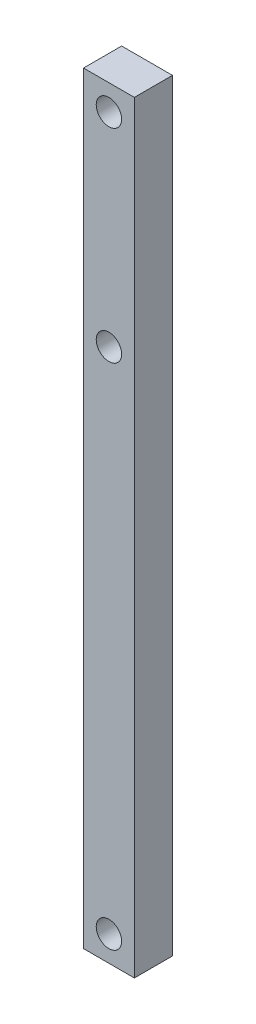
SolidWorks part; units mm, degrees
ref_plane "Front Plane" through (0, 0, 0) normal (0, 0, 1) x (1, 0, 0)
ref_plane "Top Plane" through (0, 0, 0) normal (0, 1, 0) x (1, 0, 0)
ref_plane "Right Plane" through (0, 0, 0) normal (1, 0, 0) x (0, 0, -1)
sketch "Sketch1" plane through (0, 0, 0) normal (0, 0, 1) x (1, 0, 0)
  line L1 (-10, 150) -> (10, 150)
  line L2 (-10, 150) -> (-10, -150)
  line L3 (-10, -150) -> (10, -150)
  line L4 (10, 150) -> (10, -150)
  line L5 (-10, 150) -> (10, -150) construction
  line L6 (-10, -150) -> (10, 150) construction
  circle A0 centre (0, -140) radius 5
  circle A1 centre (0, 140) radius 5
  circle A2 centre (0, 60) radius 5
  point P0 (0, 0)
  dimension "D3" = 10
  dimension "D4" = 10
  dimension "D1" = 300
  dimension "D2" = 20
  dimension "D5" = 80
extrude "Boss-Extrude1" add sketch "Sketch1" along normal blind 15 contours L2 L3 L4 L1
sketch "Sketch3" plane through (0, 0, 0) normal (0, 0, -1) x (-1, 0, 0)
  line L0 (10, 150) -> (-10, 150) construction
  line L1 (10, -150) -> (-10, -150) construction
  circle A0 centre (0, -140) radius 5
  circle A1 centre (0, 140) radius 5
  circle A2 centre (0, 60) radius 5
  dimension "D1" = 10
  dimension "D2" = 80
  dimension "D3" = 10
extrude "Cut-Extrude1" cut sketch "Sketch3" against normal blind 15
